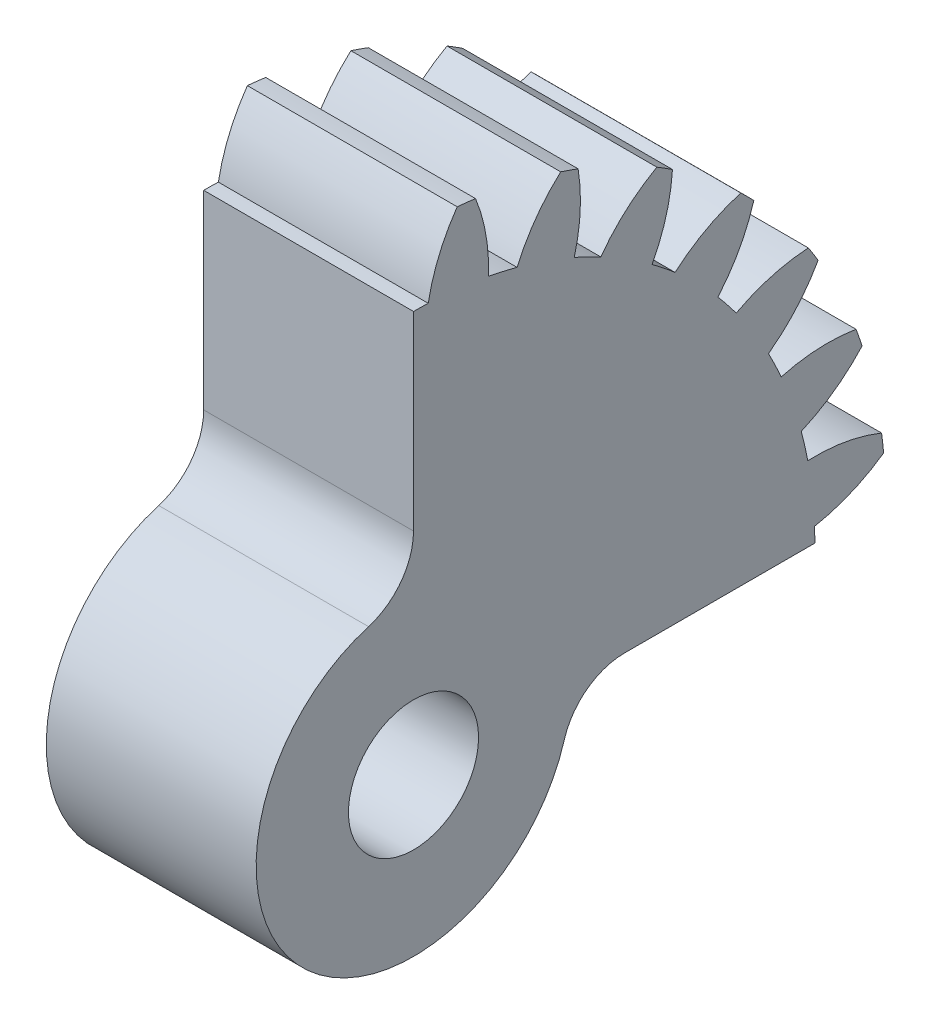
SolidWorks part; units mm, degrees
ref_plane "Plane1" through (0, 0, 0) normal (0, 0, 1) x (1, 0, 0)
ref_plane "Plane2" through (0, 0, 0) normal (0, 1, 0) x (1, 0, 0)
ref_plane "Plane3" through (0, 0, 0) normal (1, 0, 0) x (0, 0, -1)
sketch "HoldingSke" plane through (0, 0, 0) normal (0, 1, 0) x (1, 0, 0)
  line L0 (0, 0) -> (0.5886, -0.313)
  line L1 (-15, 0) -> (100, 0) construction
  line L2 (0, 0) -> (-2.1039, 2.3779)
  line L3 (0, 0) -> (-11.863, 4.5341)
  line L4 (0, 0) -> (7.6251, 4.0544)
  line L5 (0, 0) -> (-46.8476, -17.4728)
  line L6 (0, 0) -> (-8.2896, -5.593)
  line L7 (-2.1039, 2.3779) -> (8.6586, 51.2059)
  line L8 (-76.2, 54.61) -> (-73.9, 54.61)
  line L9 (-71.009, 38.7566) -> (-53.1078, 45.2721)
  line L10 (-76.2, 71.12) -> (104.1128, 71.12)
  line L11 (0, 0) -> (-10, 0)
  line L12 (-76.2, 101.6) -> (-76.147, 101.6)
  line L13 (24.9733, 27.94) -> (52.9518, 28.4284)
  line L14 (24.9733, 27.94) -> (24.9743, 27.94)
  line L15 (24.9733, 27.94) -> (100.4006, 29.5858)
  line L16 (-63.627, -1.5) -> (-12.827, -1.5)
  circle A0 centre (0, 0) radius 7.5
  circle A1 centre (0, 0) radius 19.124
  circle A2 centre (0, 0) radius 37.5
  circle A3 centre (0, 0) radius 7.5
  dimension "MHD" = 38.248
  dimension "Hub_dia" = 75
  dimension "Bore" = 15
  dimension "MBD" = 15
  dimension "Num_teeth" = 28
  dimension "Pitch_radius" = 180.3128
  dimension "Pitch" = 0.6667
  dimension "Width" = 10
  dimension "Overall_len" = 50
  dimension "Show_teeth" = 28
  dimension "Thickness" = 10
  dimension "OAL" = 50.0001
  dimension "T_dim" = 2.3
  dimension "Ap" = 20
  dimension "H" = 19.05
  dimension "Backlash" = 0.053
  dimension "Addendum_fac" = 1
  dimension "Dedendum_fac" = 1.25
  dimension "Clearance_fac" = 0.25
  dimension "Dedendum_add" = 0.001
  dimension "Module" = 1.5
sketch "BasProSke" plane through (0, 0, 0) normal (0, 1, 0) x (1, 0, 0)
  line L0 (-10, 0) -> (60, 0) construction
  line L1 (0, 0) -> (0, 22.5)
  line L2 (0, 0) -> (10, 0)
  line L3 (10, 0) -> (10, 22.5)
  line L4 (10, 22.5) -> (0, 22.5)
  dimension "Diameter" = 45
  dimension "Thickness" = 10
revolve "Base-Revolve" add sketch "BasProSke" angle 360 about L0
sketch "TooCutSke" plane through (0, 0, 0) normal (1, 0, 0) x (0, 0, -1)
  line L1 (0, 0) -> (0, 107) construction
  line L2 (0, 0) -> (-1.2702, 20.9615) construction
  line L3 (0, 0) -> (-4.6962, 41.6802) construction
  line L4 (-1.2702, 20.9615) -> (-2.3481, 20.8401) construction
  arc A0 (0.7007, 19.1112) -> (-0.7007, 19.1112) centre (0, 0) ccw
  arc A1 (2.0988, 22.4274) -> (-2.0988, 22.4274) centre (0, 0) ccw
  circle A2 centre (0, 0) radius 21 construction
  circle A3 centre (0, 0) radius 19.7335 construction
  arc A4 (-0.7007, 19.1112) -> (-2.0988, 22.4274) centre (-8.9603, 17.5819) ccw
  arc A5 (2.0988, 22.4274) -> (0.7007, 19.1112) centre (8.9603, 17.5819) ccw
  dimension "Root_dia" = 38.248
  dimension "Overcut_dia" = 45.0508
  dimension "Pitch_dia" = 42
  dimension "Base_dia" = 39.4671
  dimension "Flank_rad" = 8.4
  dimension "Half_ang" = 6.429
  dimension "Half_CT" = 1.0847
extrude "ToothCut" cut sketch "TooCutSke" along normal through all
fillet "Breaks" [suppressed] radius 0.03
fillet "RootFillets" [suppressed] radius 0.376
pattern_circular "TeethCuts" count 28 every 12.857 about axis through (-10, 0, 0) along (1, 0, 0) of "ToothCut", "RootFillets", "Breaks"
sketch "HubNeaOneSke" plane through (0, 0, 0) normal (-1, 0, 0) x (0, 0, 1)
  circle A0 centre (0, 0) radius 19.124
  dimension "Diameter" = 38.248
extrude "HubNearOne" [suppressed] add sketch "HubNeaOneSke" along normal blind 40.0001
sketch "HubNeaBotSke" plane through (0, 0, 0) normal (-1, 0, 0) x (0, 0, 1)
  circle A0 centre (0, 0) radius 19.124
  dimension "Diameter" = 38.248
extrude "HubNearBoth" [suppressed] add sketch "HubNeaBotSke" along normal blind 20
ref_plane "FarPln" through (10, 0, 0) normal (1, 0, 0) x (0, 0, -1)
sketch "HubFarSke" plane through (10, 0, 0) normal (1, 0, 0) x (0, 0, -1)
  circle A0 centre (0, 0) radius 19.124
  dimension "Diameter" = 38.248
extrude "HubFar" [suppressed] add sketch "HubFarSke" along normal blind 20
sketch "BorSke" plane through (0, 0, 0) normal (1, 0, 0) x (0, 0, -1)
  circle A0 centre (0, 0) radius 7.5
  dimension "Diameter" = 15
extrude "Bore" cut sketch "BorSke" along normal mid plane 100.0001
sketch "KeySke" plane through (0, 0, 0) normal (1, 0, 0) x (0, 0, -1)
  line L0 (-2.5, 0) -> (-2.5, 9.8)
  line L1 (-2.5, 9.8) -> (2.5, 9.8)
  line L2 (2.5, 9.8) -> (2.5, 0)
  line L3 (0, 0) -> (0, 34) construction
  line L4 (-2.5, 0) -> (2.5, 0)
  dimension "Offset" = 9.8
  dimension "Width" = 5
extrude "Keyway" [suppressed] cut sketch "KeySke" along normal mid plane 100.0001
pattern_circular "Keyway2" [suppressed] count 2 every 90 about axis through (-10, 0, 0) along (1, 0, 0)
sketch "Croquis1" plane through (10, 0, 0) normal (1, 0, 0) x (0, 0, -1)
  line L0 (0, 19.124) -> (0, 0)
  line L1 (0, 0) -> (19.124, 0)
  arc A0 (0.7007, 19.1112) -> (-0.7007, 19.1112) centre (0, 0) ccw construction
  arc A1 (19.1112, -0.7007) -> (19.1112, 0.7007) centre (0, 0) ccw construction
  arc A2 (0, 19.124) -> (19.124, 0) centre (16.9551, 16.9551) cw
extrude "Extruir1" cut sketch "Croquis1" against normal blind 10 flip side to cut
sketch "Croquis2" plane through (10, 0, 0) normal (1, 0, 0) x (0, 0, -1)
  circle A0 centre (0, 0) radius 7.5
  circle A1 centre (0, 0) radius 3.1
  dimension "D1" = 6.2
  dimension "D2" = 15
extrude "Extruir2" add sketch "Croquis2" against normal through all
fillet "Redondeo1" radius 3 2 edges at (5, 7.5, 0) (5, 0, -7.5)
equation "' \"Module@HoldingSke\" = 6.35"
equation "' \"Num_teeth@HoldingSke\" = 12"
equation "' \"Ap@HoldingSke\" =  20"
equation "' \"Width@HoldingSke\" = 0.5 * 25.4"
equation "' \"Hub_dia@HoldingSke\"= 1 * 25.4"
equation "' \"Overall_len@HoldingSke\" = 1.0 * 25.4"
equation "' \"Bore@HoldingSke\" = 0.75 * 25.4"
equation "' \"T_dim@HoldingSke\" = 0.1 * 25.4"
equation "' \"Width@KeySke\" = 0.25 * 25.4"
equation "' \"Show_teeth@HoldingSke\" = 13"
equation "' \"Backlash@HoldingSke\" = 0.009 * 25.4"
equation "' \"Addendum_fac@HoldingSke\" = 1.0"
equation "' \"Dedendum_fac@HoldingSke\" = 1.25"
equation "' \"Dedendum_add@HoldingSke\" = 0.00005 * 25.4"
equation "' \"Clearance_fac@HoldingSke\" = 0.25"
equation "\"Pitch@HoldingSke\" = 1 / \"Module@HoldingSke\""
equation "\"Overcut_dia@TooCutSke\" = (\"Num_teeth@HoldingSke\" + 2 * \"Addendum_fac@HoldingSke\") / \"Pitch@HoldingSke\" + 0.002 * 25.4"
equation "\"Pitch_dia@TooCutSke\" = \"Num_teeth@HoldingSke\" / \"Pitch@HoldingSke\""
equation "\"Base_dia@TooCutSke\" = \"Num_teeth@HoldingSke\" / \"Pitch@HoldingSke\" * cos((\"Ap@HoldingSke\"  * 3.14159265 / 180))"
equation "\"Root_dia@TooCutSke\" = (\"Num_teeth@HoldingSke\" + 2) / \"Pitch@HoldingSke\" - 2 * (\"Addendum_fac@HoldingSke\" + \"Dedendum_fac@HoldingSke\") / \"Pitch@HoldingSke\" - \"Dedendum_add@HoldingSke\" * 2"
equation "\"Half_ang@TooCutSke\" = 180 / \"Num_teeth@HoldingSke\""
equation "\"Half_CT@TooCutSke\" = \"Num_teeth@HoldingSke\" / \"Pitch@HoldingSke\" * sin((3.14159265 / 2 / \"Num_teeth@HoldingSke\")) / 2 - 7 * \"Backlash@HoldingSke\" / 4"
equation "\"Flank_rad@TooCutSke\" = \"Num_teeth@HoldingSke\" / \"Pitch@HoldingSke\" / 5"
equation "\"Radius@RootFillets\" = \"Clearance_fac@HoldingSke\" / \"Pitch@HoldingSke\" + \"Dedendum_add@HoldingSke\""
equation "\"Break_rad@Breaks\" = 0.02 / \"Pitch@HoldingSke\""
equation "\"Thickness@HoldingSke\" = \"Width@HoldingSke\""
equation "\"OAL@HoldingSke\" = \"Thickness@HoldingSke\""
equation "\"MHD@HoldingSke\" = (\"Num_teeth@HoldingSke\" + 2) / \"Pitch@HoldingSke\" - 2 * (\"Addendum_fac@HoldingSke\" + \"Dedendum_fac@HoldingSke\")  / \"Pitch@HoldingSke\" - \"Dedendum_add@HoldingSke\" * 2"
equation "\"MBD@HoldingSke\" = (\"Num_teeth@HoldingSke\" + 2) / \"Pitch@HoldingSke\" - 2 * (\"Addendum_fac@HoldingSke\" + \"Dedendum_fac@HoldingSke\")  / \"Pitch@HoldingSke\" - \"Dedendum_add@HoldingSke\" * 2 - 0.002 * 25.4"
equation "\"MHD@HoldingSke\" = ((sgn( \"MHD@HoldingSke\" - \"Hub_dia@HoldingSke\" )-1)*( \"MHD@HoldingSke\" - \"Hub_dia@HoldingSke\" ))/-2+ \"Hub_dia@HoldingSke\""
equation "\"MBD@HoldingSke\" = ((sgn( \"MBD@HoldingSke\" - \"Bore@HoldingSke\" )-1)*( \"MBD@HoldingSke\" - \"Bore@HoldingSke\" ))/-2+ \"Bore@HoldingSke\""
equation "\"OAL@HoldingSke\" = ((sgn( \"OAL@HoldingSke\" - \"Overall_len@HoldingSke\" )+1)*( \"OAL@HoldingSke\" - \"Overall_len@HoldingSke\" ))/2 + \"Overall_len@HoldingSke\" + 0.000002 * 25.4"
equation "\"Num_teeth@TeethCuts\" = int( \"Show_teeth@HoldingSke\" ) + 1"
equation "\"Num_teeth@TeethCuts\" = ((sgn( \"Num_teeth@TeethCuts\" - \"Num_teeth@HoldingSke\" )-1)*( \"Num_teeth@TeethCuts\" - \"Num_teeth@HoldingSke\" ))/-2+ \"Num_teeth@HoldingSke\""
equation "\"Num_teeth@TeethCuts\" = ((sgn( \"Num_teeth@TeethCuts\" - 2.0)+1)*( \"Num_teeth@TeethCuts\" - 2.0))/2 +2.0"
equation "\"Angle@TeethCuts\" = 360.0 / \"Num_teeth@HoldingSke\""
equation "\"Diameter@BasProSke\" = (\"Num_teeth@HoldingSke\" + 2 * \"Addendum_fac@HoldingSke\") / \"Pitch@HoldingSke\""
equation "\"Thickness@BasProSke\"  = \"Thickness@HoldingSke\""
equation "' \"Fillet_rad@BasProSke\" =  \"Thickness@HoldingSke\" * 0.05"
equation "\"MHD@HoldingSke\" = ((sgn( \"MHD@HoldingSke\" - \"Root_dia@TooCutSke\" )-1)*( \"MHD@HoldingSke\" - \"Root_dia@TooCutSke\" ))/-2+ \"Root_dia@TooCutSke\""
equation "\"Diameter@HubNeaOneSke\" = \"MHD@HoldingSke\""
equation "\"Length@HubNearOne\" = \"OAL@HoldingSke\" - \"Thickness@BasProSke\""
equation "\"Diameter@HubNeaBotSke\" = \"MHD@HoldingSke\""
equation "\"Length@HubNearBoth\" = ( \"OAL@HoldingSke\" - \"Thickness@BasProSke\" ) / 2.0"
equation "\"Thickness@FarPln\" = \"Thickness@BasProSke\""
equation "\"Diameter@HubFarSke\" = \"MHD@HoldingSke\""
equation "\"Length@HubFar\" = ( \"OAL@HoldingSke\" - \"Thickness@BasProSke\" ) / 2.0"
equation "\"Diameter@BorSke\" = \"MBD@HoldingSke\""
equation "\"D1@Bore\" = \"OAL@HoldingSke\" * 2.0"
equation "\"D1@Keyway\" = \"OAL@HoldingSke\" * 2.0"
equation "\"Offset@KeySke\" = \"T_dim@HoldingSke\" + \"MBD@HoldingSke\" / 2.0"
